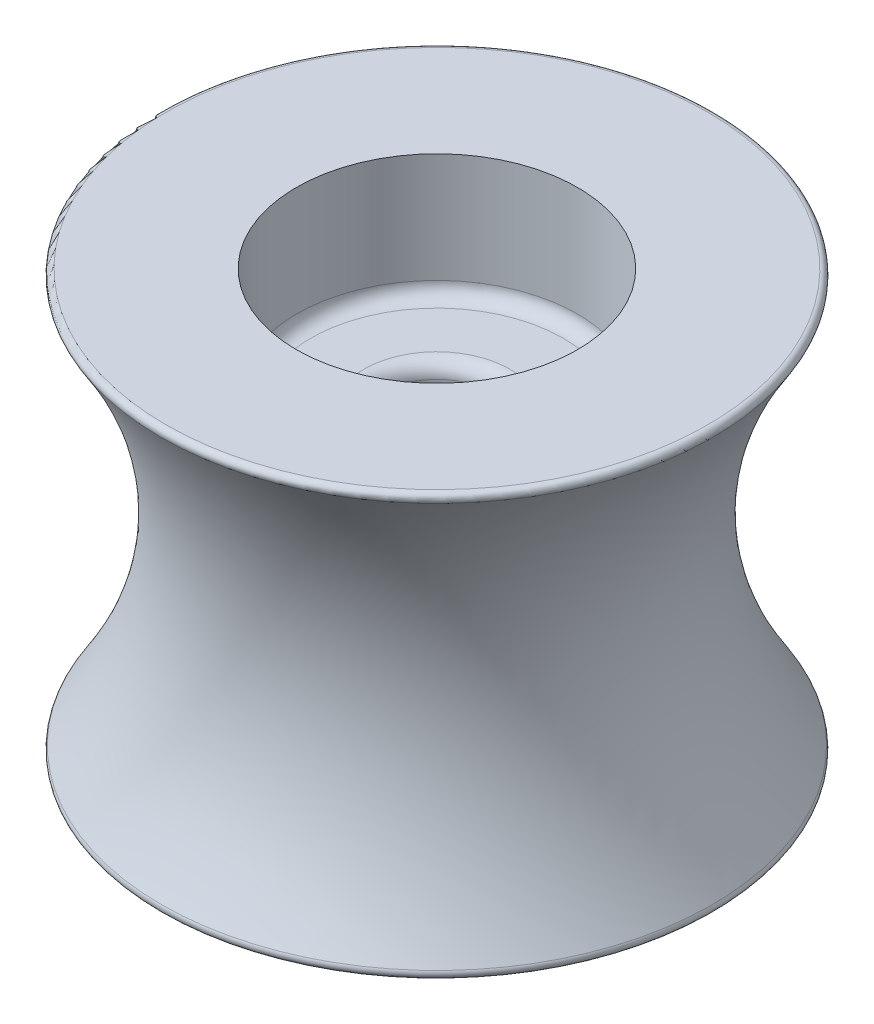
SolidWorks part; units mm, degrees
ref_plane "Front" through (0, 0, 0) normal (0, 0, 1) x (1, 0, 0)
ref_plane "Top" through (0, 0, 0) normal (0, 1, 0) x (1, 0, 0)
ref_plane "Right" through (0, 0, 0) normal (1, 0, 0) x (0, 0, -1)
sketch "Sketch1" plane through (0, 0, 0) normal (0, 0, 1) x (1, 0, 0)
  line L0 (0, 9.525) -> (0, -9.525)
  line L1 (0, 9.525) -> (12.7, 9.525)
  line L2 (0, -9.525) -> (12.7, -9.525)
  line L3 (0, 0) -> (9.525, 0) construction
  spline S0 degree 2 poles (12.7, 9.525) (6.35, 0) (12.7, -9.525) knots 0 0 0 1 1 1
  dimension "D3" = 9.525
  dimension "D1" = 12.7
  dimension "D2" = 19.05
revolve "Revolve2" add sketch "Sketch1" angle 360 about L0
sketch "Sketch2" plane through (0, 9.525, 0) normal (0, 1, 0) x (1, 0, 0)
  circle A0 centre (0, 0) radius 2.667
  dimension "D1" = 5.334
extrude "Cut-Extrude1" cut sketch "Sketch2" against normal through all both and the other way through all
sketch "Sketch3" plane through (0, 9.525, 0) normal (0, 1, 0) x (1, 0, 0)
  circle A0 centre (0, 0) radius 6.35
  dimension "D1" = 12.7
extrude "Cut-Extrude2" cut sketch "Sketch3" against normal blind 5.588
mirror "Mirror1" about plane through (0, 0, 0) normal (0, 1, 0) of "Cut-Extrude2"
fillet "Fillet1" radius 0.254 2 edges at (0, -9.525, 12.7) (0, 9.525, 12.7)
fillet "Fillet2" radius 0.635 2 edges at (0, -3.937, 6.35) (0, 3.937, 6.35)
fillet "Fillet3" radius 0.635 2 edges at (0, -3.937, -2.667) (0, 3.937, 2.667)
